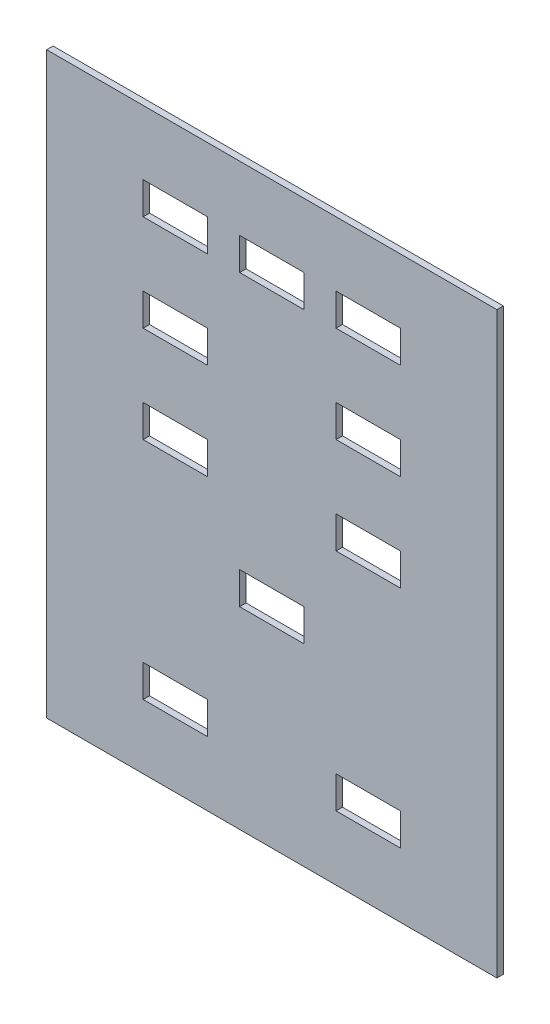
SolidWorks part; units mm, degrees
material "Brass"
ref_plane "Front Plane" through (0, 0, 0) normal (0, 0, 1) x (1, 0, 0)
ref_plane "Top Plane" through (0, 0, 0) normal (0, 1, 0) x (1, 0, 0)
ref_plane "Right Plane" through (0, 0, 0) normal (1, 0, 0) x (0, 0, -1)
sketch "Sketch1" plane through (0, 0, 0) normal (0, 0, 1) x (1, 0, 0)
  line L1 (0, 0) -> (350, 0)
  line L2 (0, 0) -> (0, 450)
  line L3 (0, 450) -> (350, 450)
  line L4 (350, 0) -> (350, 450)
  dimension "D1" = 350
  dimension "D2" = 450
extrude "Boss-Extrude1" add sketch "Sketch1" along normal blind 5
sketch "Sketch2" plane through (0, 0, 5) normal (0, 0, 1) x (1, 0, 0)
  line L2 (75, 375) -> (125, 375)
  line L3 (75, 375) -> (75, 400)
  line L4 (75, 400) -> (125, 400)
  line L5 (350, 450) -> (0, 450) construction
  line L6 (175, 450) -> (175, 207.535) construction
  line L7 (125, 375) -> (125, 400)
  line L8 (75, 375) -> (125, 400) construction
  line L9 (75, 400) -> (125, 375) construction
  point P0 (100, 387.5)
  dimension "D1" = 150
  dimension "D2" = 50
  dimension "D3" = 25
  dimension "D4" = 50
extrude "Cut-Extrude1" cut sketch "Sketch2" against normal through all
sketch "Sketch3" plane through (0, 0, 5) normal (0, 0, 1) x (1, 0, 0)
  line L0 (125, 387.5) -> (305.2264, 387.5) construction
  line L1 (125, 375) -> (125, 400) construction
  line L2 (100, 375) -> (100, 49.8189) construction
  line L3 (75, 375) -> (125, 375) construction
  line L4 (125, 387.5) -> (75, 387.5) construction
  line L5 (75, 400) -> (75, 375) construction
  line L6 (100, 375) -> (100, 400) construction
  line L7 (125, 400) -> (75, 400) construction
  point P8 (175, 387.5)
  point P9 (250, 387.5)
  point P10 (100, 312.5)
  point P11 (100, 237.5)
  point P13 (100, 62.5)
  point P14 (250, 312.5)
  point P21 (250, 237.5)
  point P22 (175, 162.5)
  point P23 (0, 0)
  point P24 (250, 62.5)
  point P25 (0, 0)
  point P26 (0, 0)
  point P27 (0, 0)
  dimension "D1" = 75
  dimension "D2" = 150
  dimension "D3" = 75
  dimension "D4" = 150
  dimension "D5" = 225
  dimension "D6" = 325
pattern_sketch "Sketch-Pattern1" of "Cut-Extrude1" driven by "Sketch3"
